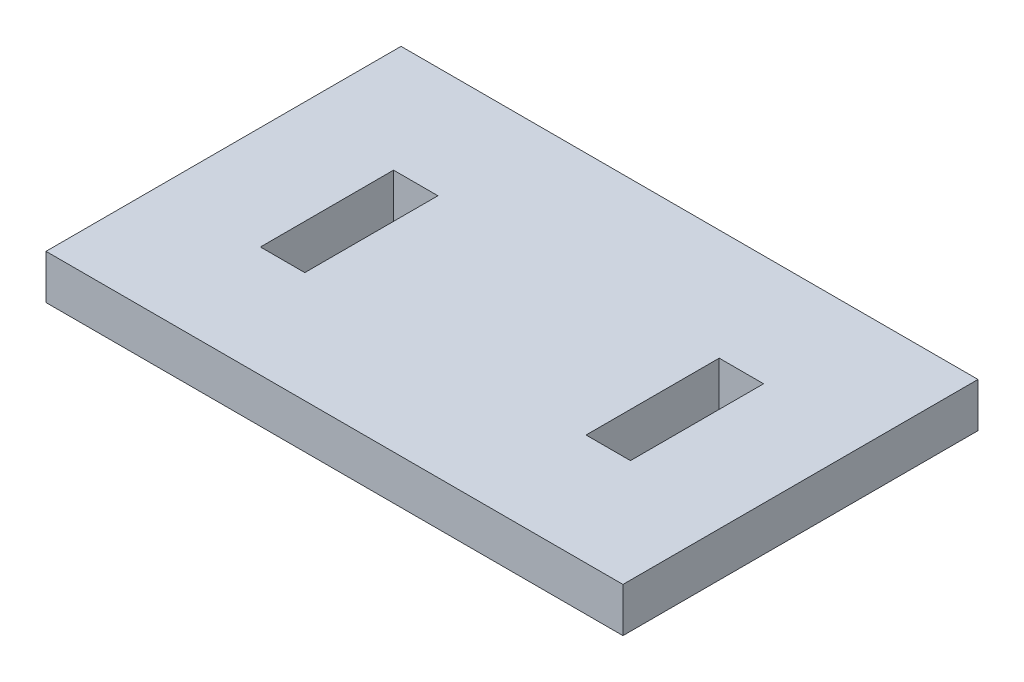
SolidWorks part; units mm, degrees
ref_plane "Front Plane" through (0, 0, 0) normal (0, 0, 1) x (1, 0, 0)
ref_plane "Top Plane" through (0, 0, 0) normal (0, 1, 0) x (1, 0, 0)
ref_plane "Right Plane" through (0, 0, 0) normal (1, 0, 0) x (0, 0, -1)
sketch "Sketch1" plane through (0, 0, 0) normal (0, 1, 0) x (1, 0, 0)
  line L0 (7.4013, 12.7) -> (0, 12.7) construction
  line L1 (0, 0) -> (41.275, 0)
  line L2 (0, 0) -> (0, 25.4)
  line L3 (0, 25.4) -> (41.275, 25.4)
  line L4 (41.275, 0) -> (41.275, 25.4)
  line L5 (7.4013, 17.4625) -> (10.5763, 17.4625)
  line L6 (7.4013, 17.4625) -> (7.4013, 7.9375)
  line L7 (7.4013, 7.9375) -> (10.5763, 7.9375)
  line L8 (10.5763, 17.4625) -> (10.5763, 7.9375)
  line L9 (20.6375, 25.4) -> (20.6375, 0) construction
  line L10 (33.8737, 7.9375) -> (30.6987, 7.9375)
  line L11 (30.6987, 17.4625) -> (30.6987, 7.9375)
  line L12 (33.8737, 17.4625) -> (30.6987, 17.4625)
  line L13 (33.8737, 17.4625) -> (33.8737, 7.9375)
  dimension "D1" = 25.4
  dimension "D2" = 41.275
  dimension "D3" = 3.175
  dimension "D4" = 9.525
extrude "Boss-Extrude1" add sketch "Sketch1" along normal blind 3.175
